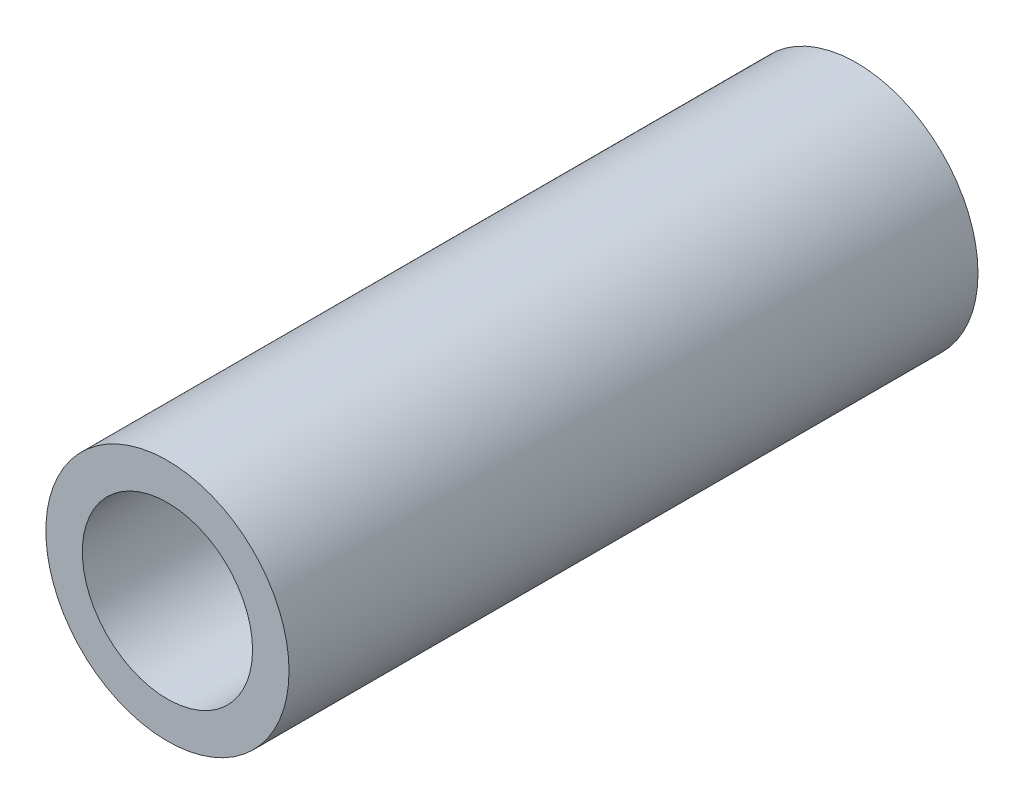
SolidWorks part; units mm, degrees
ref_plane "Front Plane" through (0, 0, 0) normal (0, 0, 1) x (1, 0, 0)
ref_plane "Top Plane" through (0, 0, 0) normal (0, 1, 0) x (1, 0, 0)
ref_plane "Right Plane" through (0, 0, 0) normal (1, 0, 0) x (0, 0, -1)
sketch "Sketch1" plane through (0, 0, 0) normal (0, 0, 1) x (1, 0, 0)
  circle A0 centre (0, 0) radius 2.1
  circle A1 centre (0, 0) radius 3
  dimension "D1" = 4.2
  dimension "D2" = 6
extrude "Boss-Extrude1" add sketch "Sketch1" along normal blind 17
equation "\"iw\"= 4.2mm'o"
equation "\"ow\"= 6mm"
equation "\"h\"= 17mm"
equation "\"D1@Sketch1\"=\"iw\""
equation "\"D2@Sketch1\"=\"ow\""
equation "\"D1@Boss-Extrude1\"=\"h\""
